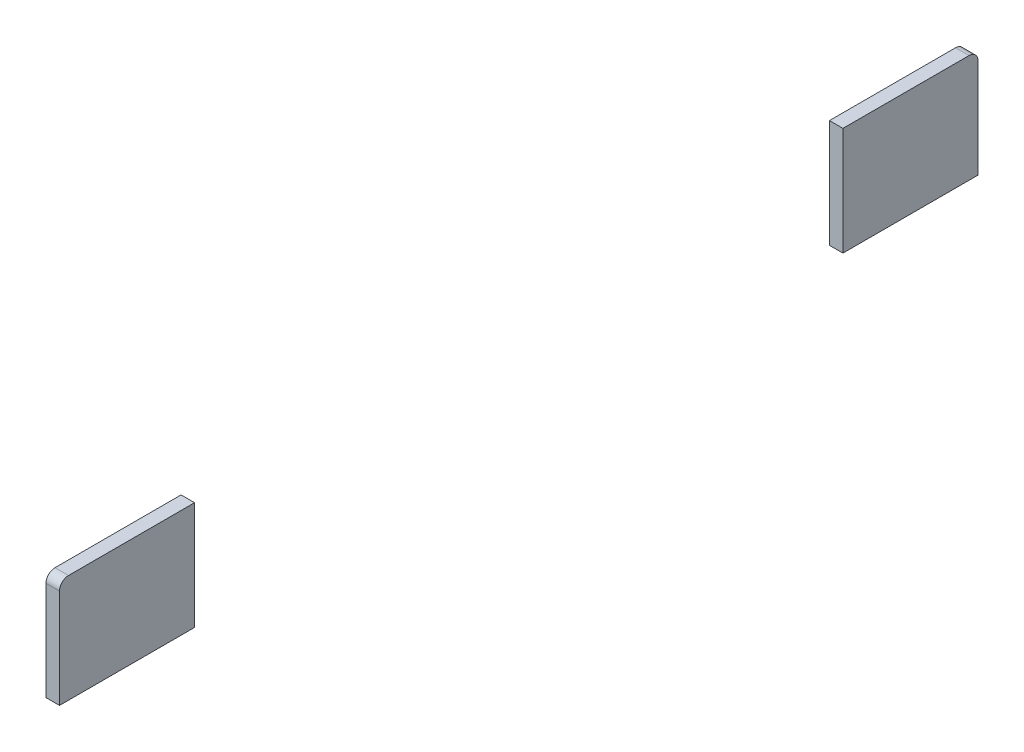
SolidWorks part; units mm, degrees
ref_plane "Front Plane" through (0, 0, 0) normal (0, 0, 1) x (1, 0, 0)
ref_plane "Top Plane" through (0, 0, 0) normal (0, 1, 0) x (1, 0, 0)
ref_plane "Right Plane" through (0, 0, 0) normal (1, 0, 0) x (0, 0, -1)
sketch "Sketch1" plane through (0, 0, 0) normal (1, 0, 0) x (0, 0, -1)
  line L0 (0, 0) -> (15, 0)
  line L1 (15, 0) -> (15, 11)
  line L2 (0, 0) -> (0, 12)
  line L3 (0, 12) -> (14, 12)
  line L4 (0, 0) -> (-72, 0) construction
  line L5 (-36, 0) -> (-36, 14.9463) construction
  line L6 (-87, 0) -> (-87, 11)
  line L7 (-72, 0) -> (-87, 0)
  line L8 (-72, 0) -> (-72, 12)
  line L9 (-72, 12) -> (-86, 12)
  arc A0 (14, 12) -> (15, 11) centre (14, 11) cw
  arc A1 (-86, 12) -> (-87, 11) centre (-86, 11) ccw
  dimension "D1" = 11
extrude "Boss-Extrude1" add sketch "Sketch1" along normal blind 1.5
